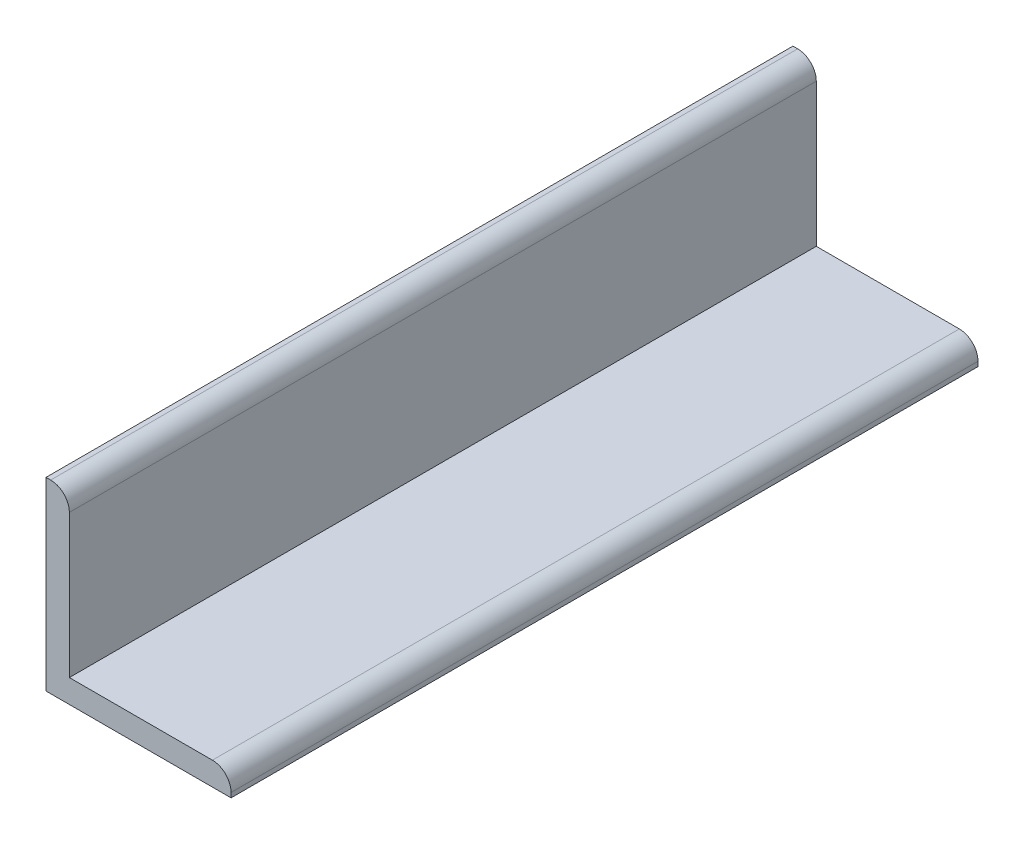
SolidWorks part; units mm, degrees
ref_plane "Front Plane" through (0, 0, 0) normal (0, 0, 1) x (1, 0, 0)
ref_plane "Top Plane" through (0, 0, 0) normal (0, 1, 0) x (1, 0, 0)
ref_plane "Right Plane" through (0, 0, 0) normal (1, 0, 0) x (0, 0, -1)
sketch "Sketch1" plane through (0, 0, 0) normal (0, 0, 1) x (1, 0, 0)
  line L1 (0, 0) -> (50.3426, 0)
  line L2 (0, 0) -> (0, 50.3426)
  line L3 (0, 50.3426) -> (1.27, 50.3426)
  line L4 (50.3426, 0) -> (50.3426, 1.27)
  line L5 (0, 0) -> (50.3426, 50.3426) construction
  line L6 (0, 50.3426) -> (50.3426, 0) construction
  line L7 (50.3426, 50.3426) -> (6.35, 50.3426)
  line L8 (50.3426, 50.3426) -> (50.3426, 6.35)
  line L9 (45.2626, 6.35) -> (6.35, 6.35)
  line L10 (6.35, 45.2626) -> (6.35, 6.35)
  line L11 (50.3426, 50.3426) -> (6.35, 6.35) construction
  line L12 (50.3426, 6.35) -> (6.35, 50.3426) construction
  arc A0 (50.3426, 1.27) -> (45.2626, 6.35) centre (45.2626, 1.27) ccw
  arc A1 (1.27, 50.3426) -> (6.35, 45.2626) centre (1.27, 45.2626) cw
  point P4 (25.1713, 25.1713)
  point P5 (7.8391, 6.35)
  point P10 (28.3463, 28.3463)
  dimension "D3" = 5.08
  dimension "D1" = 6.35
  dimension "D2" = 6.35
extrude "Boss-Extrude1" add sketch "Sketch1" along normal blind 203.2 contours A1 L3 L2 L1 L4 A0 L9 L10
